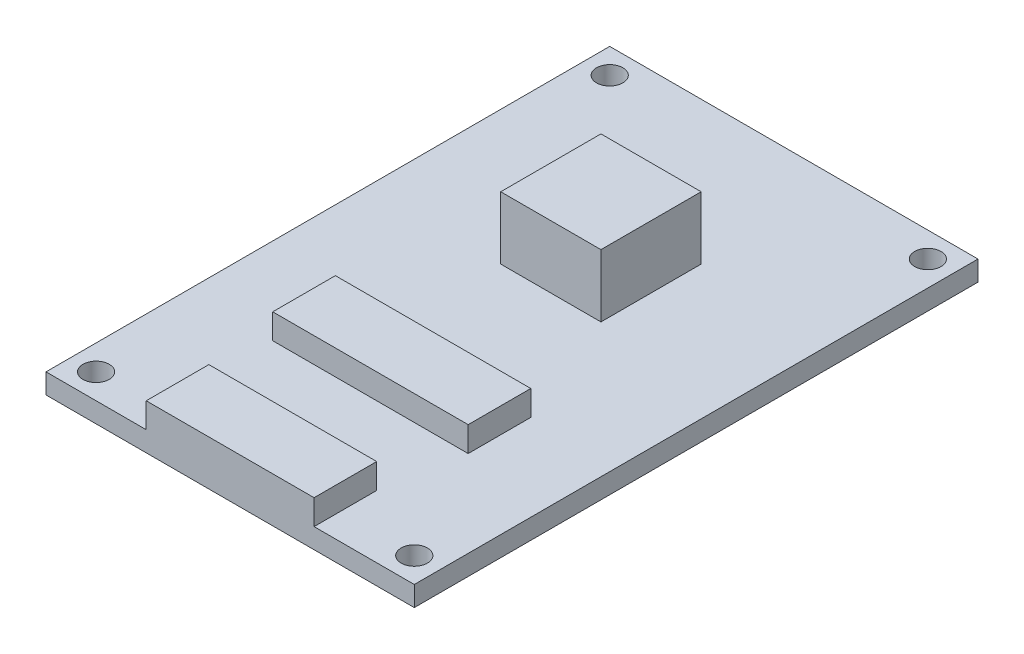
SolidWorks part; units mm, degrees
ref_plane "前视基准面" through (0, 0, 0) normal (0, 0, 1) x (1, 0, 0)
ref_plane "上视基准面" through (0, 0, 0) normal (0, 1, 0) x (1, 0, 0)
ref_plane "右视基准面" through (0, 0, 0) normal (1, 0, 0) x (0, 0, -1)
sketch "草图2" plane through (0, 0, 0) normal (0, 1, 0) x (1, 0, 0)
  line L0 (2, 45) -> (2, 0) construction
  line L1 (0, 0) -> (29.4, 0)
  line L2 (0, 0) -> (0, 45)
  line L3 (0, 45) -> (29.4, 45)
  line L4 (29.4, 0) -> (29.4, 45)
  line L5 (27.4, 45) -> (27.4, 0) construction
  line L6 (29.4, 43) -> (0, 43) construction
  line L7 (29.4, 2) -> (0, 2) construction
  circle A0 centre (2, 43) radius 1.05
  circle A1 centre (27.4, 43) radius 1.05
  circle A2 centre (2, 2) radius 1.05
  circle A3 centre (27.4, 2) radius 1.05
  dimension "D7" = 2.1
  dimension "D8" = 2.1
  dimension "D9" = 2.1
  dimension "D10" = 2.1
  dimension "D1" = 29.4
  dimension "D2" = 45
  dimension "D3" = 2
  dimension "D4" = 2
  dimension "D5" = 2
  dimension "D6" = 2
extrude "凸台-拉伸1" add sketch "草图2" along normal blind 1.6
sketch "草图3" plane through (0, 1.6, 0) normal (0, 1, 0) x (1, 0, 0)
  line L0 (0, 0) -> (29.4, 0) construction
  line L1 (8, 0) -> (21.4, 0)
  line L2 (8, 0) -> (8, 5)
  line L3 (8, 5) -> (21.4, 5)
  line L4 (21.4, 0) -> (21.4, 5)
  line L5 (0, 45) -> (0, 0) construction
  line L7 (6.9, 11.2) -> (22.5, 11.2)
  line L8 (6.9, 11.2) -> (6.9, 16.2)
  line L9 (6.9, 16.2) -> (22.5, 16.2)
  line L10 (22.5, 11.2) -> (22.5, 16.2)
  dimension "D1" = 8
  dimension "D2" = 13.4
  dimension "D3" = 5
  dimension "D4" = 6.9
  dimension "D5" = 15.6
  dimension "D6" = 5
  dimension "D7" = 11.2
extrude "凸台-拉伸2" add sketch "草图3" along normal blind 2
sketch "草图4" plane through (0, 0, 0) normal (0, -1, 0) x (1, 0, 0)
  line L0 (29.4, 0) -> (29.4, -45) construction
  line L1 (7.4, -2.3) -> (22.1, -2.3)
  line L2 (7.4, -2.3) -> (7.4, -6.3)
  line L3 (7.4, -6.3) -> (22.1, -6.3)
  line L4 (22.1, -2.3) -> (22.1, -6.3)
  line L5 (0, 0) -> (29.4, 0) construction
  dimension "D1" = 7.3
  dimension "D2" = 2.3
  dimension "D3" = 14.7
  dimension "D4" = 4
extrude "凸台-拉伸3" add sketch "草图4" along normal blind 2
sketch "草图5" plane through (0, 1.6, 0) normal (0, 1, 0) x (1, 0, 0)
  line L0 (0, 45) -> (0, 0) construction
  line L1 (10.7, 33.6) -> (18.7, 33.6)
  line L2 (10.7, 33.6) -> (10.7, 25.6)
  line L3 (10.7, 25.6) -> (18.7, 25.6)
  line L4 (18.7, 33.6) -> (18.7, 25.6)
  line L5 (29.4, 45) -> (0, 45) construction
  dimension "D1" = 10.7
  dimension "D2" = 11.4
  dimension "D3" = 8
  dimension "D4" = 8
extrude "凸台-拉伸4" add sketch "草图5" along normal blind 5
